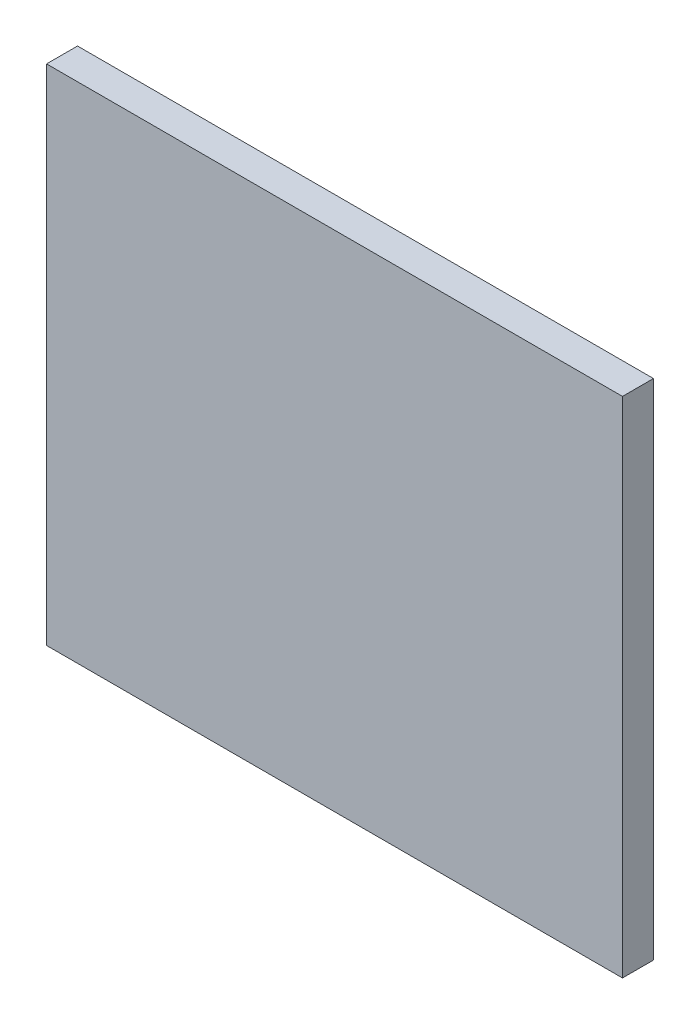
SolidWorks part; units mm, degrees
ref_plane "Alzado" through (0, 0, 0) normal (1, 0, 0) x (0, 1, 0)
ref_plane "Planta" through (0, 0, 0) normal (0, 0, 1) x (0, 1, 0)
ref_plane "Vista lateral" through (0, 0, 0) normal (0, 1, 0) x (-1, 0, 0)
sketch "Croquis2" plane through (0, 0, 0) normal (0, 0, 1) x (0, 1, 0)
  line L1 (0, 0) -> (244, 0)
  line L2 (0, 0) -> (0, 279)
  line L3 (0, 279) -> (244, 279)
  line L4 (244, 0) -> (244, 279)
  dimension "D1" = 244
  dimension "D2" = 279
extrude "Saliente-Extruir1" add sketch "Croquis2" along normal blind 15
